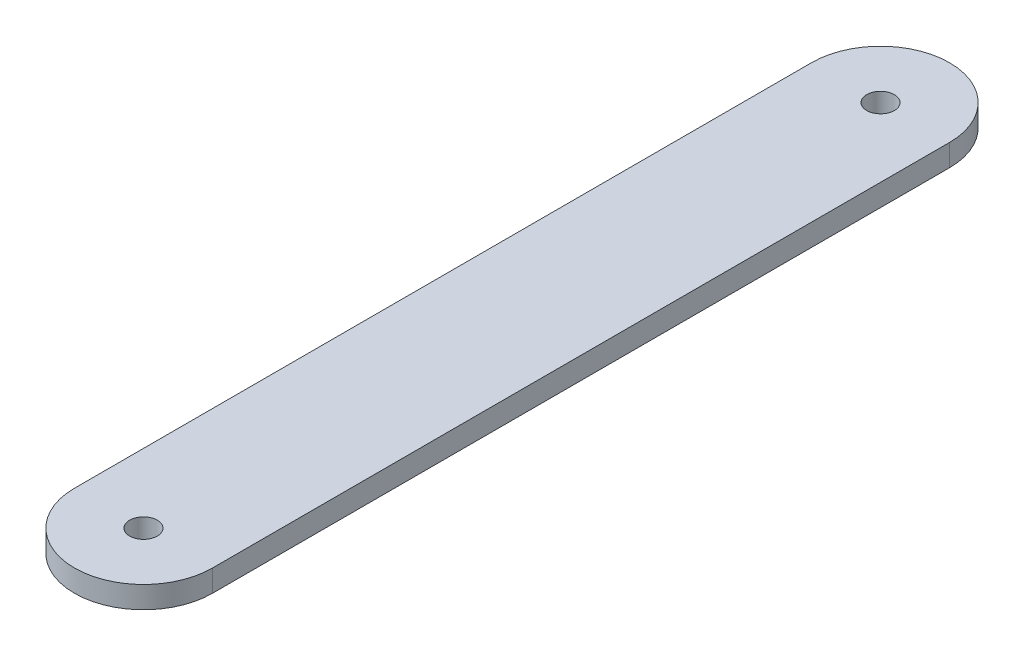
SolidWorks part; units mm, degrees
ref_plane "Front Plane" through (0, 0, 0) normal (0, 0, 1) x (1, 0, 0)
ref_plane "Top Plane" through (0, 0, 0) normal (0, 1, 0) x (1, 0, 0)
ref_plane "Right Plane" through (0, 0, 0) normal (1, 0, 0) x (0, 0, -1)
sketch "Sketch2" plane through (0, 0, 0) normal (0, 1, 0) x (1, 0, 0)
  line L0 (-5, 53.3739) -> (-5, 0)
  line L1 (5, 53.3739) -> (5, 0)
  circle A0 centre (0, 0) radius 1
  circle A1 centre (0, 53.3739) radius 1
  arc A2 (5, 0) -> (-5, 0) centre (0, 0) cw
  arc A3 (5, 53.3739) -> (-5, 53.3739) centre (0, 53.3739) ccw
  dimension "D2" = 2
  dimension "D3" = 5
  dimension "D1" = 53.3739
extrude "Boss-Extrude1" add sketch "Sketch2" along normal blind 1.5875
